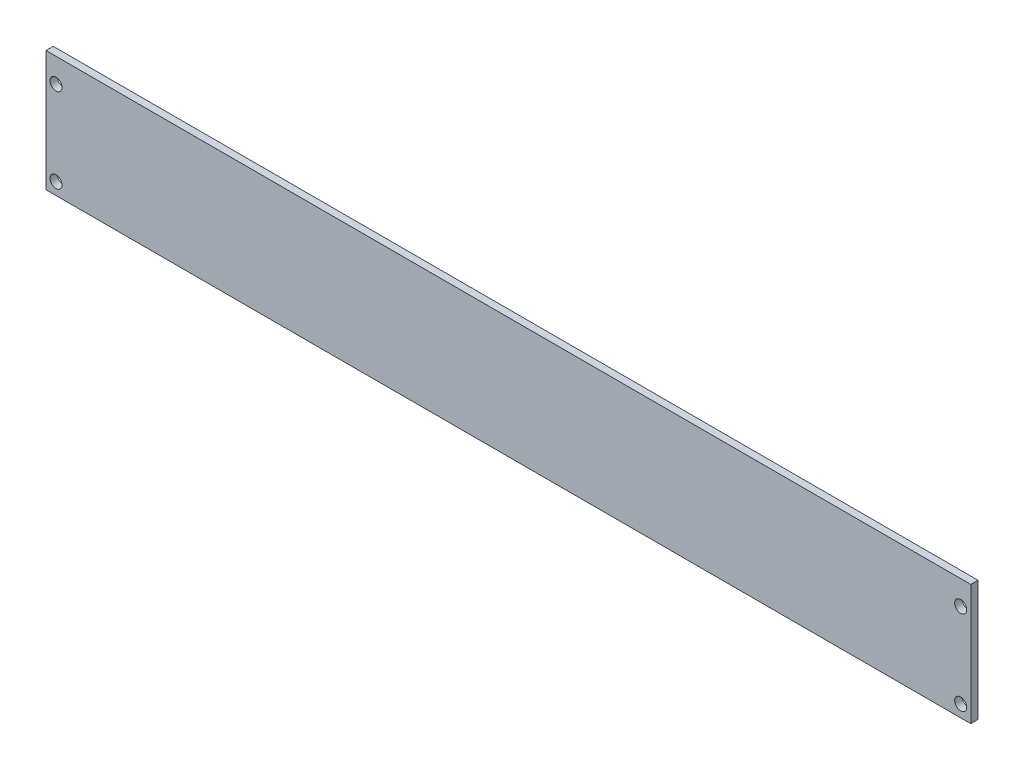
SolidWorks part; units mm, degrees
material "AISI 4130 Steel, normalized at 870C"
ref_plane "Front Plane" through (0, 0, 0) normal (0, 0, 1) x (1, 0, 0)
ref_plane "Top Plane" through (0, 0, 0) normal (0, 1, 0) x (1, 0, 0)
ref_plane "Right Plane" through (0, 0, 0) normal (1, 0, 0) x (0, 0, -1)
sketch "Sketch1" plane through (0, 0, 0) normal (0, 0, 1) x (1, 0, 0)
  line L0 (-142.875, 11.43) -> (-142.875, -15.24) construction
  line L1 (146.05, 19.05) -> (-146.05, 19.05)
  line L2 (146.05, 19.05) -> (146.05, -19.05)
  line L3 (146.05, -19.05) -> (-146.05, -19.05)
  line L4 (-146.05, 19.05) -> (-146.05, -19.05)
  line L5 (146.05, 19.05) -> (-146.05, -19.05) construction
  line L6 (146.05, -19.05) -> (-146.05, 19.05) construction
  line L7 (-142.875, 11.43) -> (142.875, 11.43) construction
  circle A2 centre (-142.875, 11.43) radius 1.8987
  circle A3 centre (-142.875, -15.24) radius 1.8987
  circle A4 centre (142.875, 11.43) radius 1.8987
  circle A5 centre (142.875, -15.24) radius 1.8987
  point P0 (0, 0)
  point P8 (-142.875, -1.905)
  point P15 (0, 11.43)
  point P16 (0, 0)
  dimension "D3" = 3.175
  dimension "D4" = 3.7973
  dimension "D1" = 38.1
  dimension "D2" = 292.1
  dimension "D5" = 7.62
  dimension "D6" = 34.29
extrude "Boss-Extrude1" add sketch "Sketch1" along normal blind 2.286
